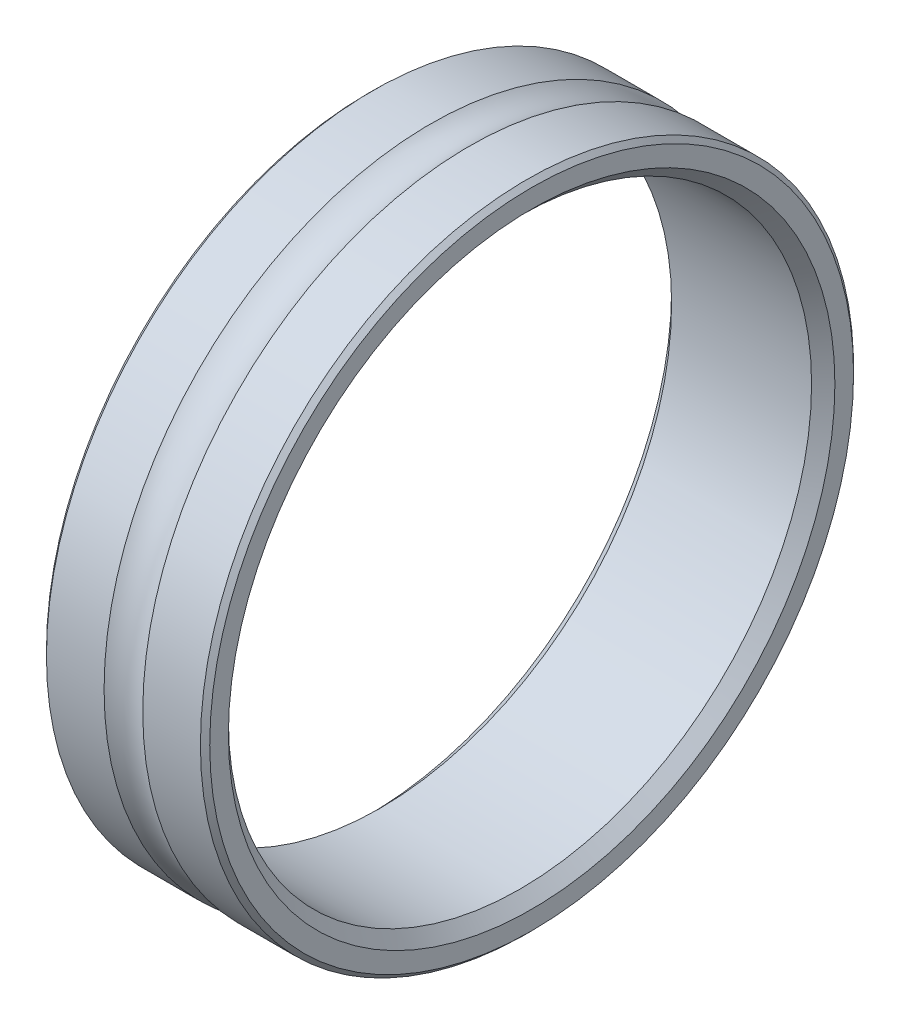
SolidWorks part; units mm, degrees
ref_plane "Спереди" through (0, 0, 0) normal (0, 0, 1) x (1, 0, 0)
ref_plane "Сверху" through (0, 0, 0) normal (0, 1, 0) x (1, 0, 0)
ref_plane "Справа" through (0, 0, 0) normal (1, 0, 0) x (0, 0, -1)
sketch "Эскиз1" plane through (0, 0, 0) normal (0, 0, 1) x (1, 0, 0)
  line L0 (0, 0) -> (53.2167, 0) construction
  line L1 (0, 0) -> (0, 43.2928) construction
  line L2 (0.8292, 14) -> (3.5, 14)
  line L3 (-3.5, 12.5) -> (3.5, 12.5)
  line L4 (-3.5, 12.5) -> (-3.5, 14)
  line L5 (-3.5, 14) -> (-0.8292, 14)
  line L6 (3.5, 12.5) -> (3.5, 14)
  arc A0 (-0.8292, 14) -> (0.8292, 14) centre (0, 15.25) ccw
  dimension "D4" = 3
  dimension "D5" = 1.25
  dimension "D1" = 7
  dimension "D2" = 1.5
  dimension "D3" = 25
revolve "Повернуть1" add sketch "Эскиз1" angle 360 about L0
chamfer "Фаска1" distance 0.5 angle 45 2 edges at (-3.5, 0, 12.5) (3.5, 0, 12.5)
chamfer "Фаска2" distance 0.2 angle 45 2 edges at (-3.5, 0, 14) (3.5, 0, 14)
